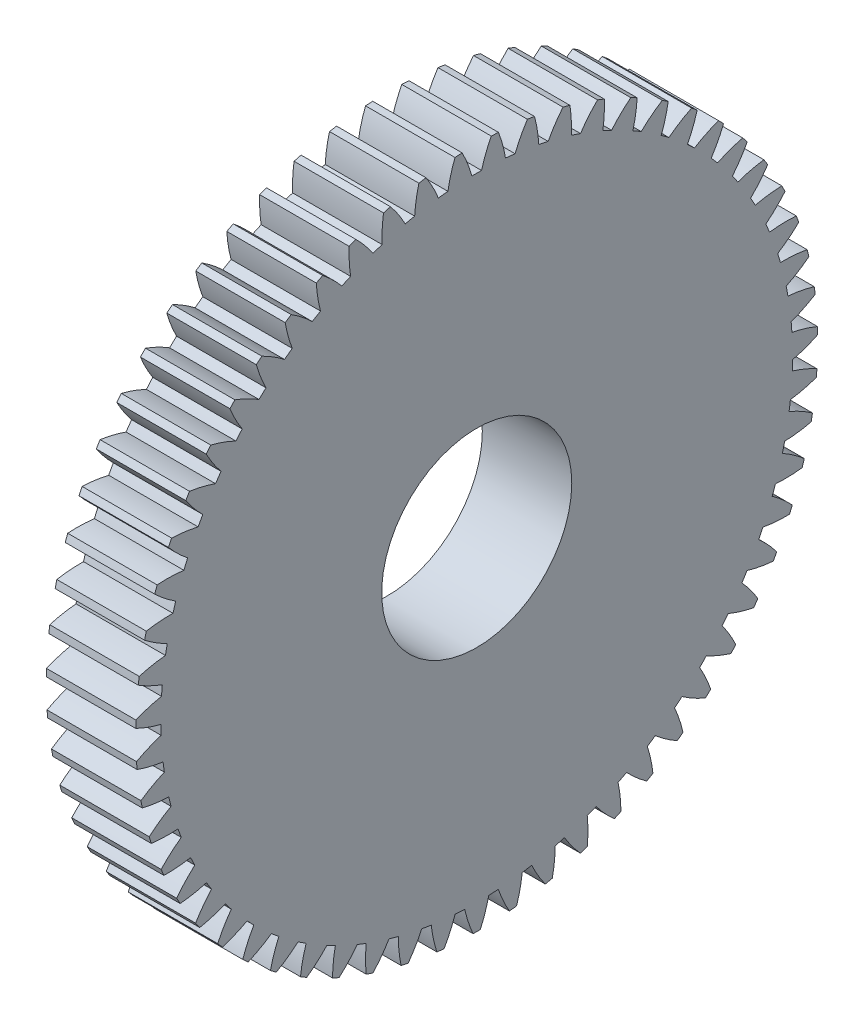
SolidWorks part; units mm, degrees
material "ABS PC"
ref_plane "Plane1" through (0, 0, 0) normal (0, 0, 1) x (1, 0, 0)
ref_plane "Plane2" through (0, 0, 0) normal (0, 1, 0) x (1, 0, 0)
ref_plane "Plane3" through (0, 0, 0) normal (1, 0, 0) x (0, 0, -1)
sketch "HoldingSke" plane through (0, 0, 0) normal (0, 1, 0) x (1, 0, 0)
  line L0 (0, 0) -> (1.0301, -1.7143)
  line L1 (-15, 0) -> (100, 0) construction
  line L2 (0, 0) -> (-2.1039, 2.3779)
  line L3 (0, 0) -> (-11.863, 4.5341)
  line L4 (0, 0) -> (4.4479, 7.4025)
  line L5 (0, 0) -> (-46.8476, -17.4728)
  line L6 (0, 0) -> (-3.3159, -2.2372)
  line L7 (-2.1039, 2.3779) -> (8.6586, 51.2059)
  line L8 (-76.2, 54.61) -> (-75.3, 54.61)
  line L9 (-71.009, 38.7566) -> (-53.1078, 45.2721)
  line L10 (-76.2, 71.12) -> (104.1128, 71.12)
  line L11 (0, 0) -> (-4, 0)
  line L12 (-76.2, 101.6) -> (-76.181, 101.6)
  line L13 (24.9733, 27.94) -> (52.9518, 28.4284)
  line L14 (24.9733, 27.94) -> (24.9743, 27.94)
  line L15 (24.9733, 27.94) -> (100.4006, 29.5858)
  line L16 (-63.627, -0.5) -> (-12.827, -0.5)
  circle A0 centre (0, 0) radius 2.5
  circle A1 centre (0, 0) radius 14.124
  circle A2 centre (0, 0) radius 37.5
  circle A3 centre (0, 0) radius 2.5
  dimension "MHD" = 28.248
  dimension "Hub_dia" = 75
  dimension "Bore" = 5
  dimension "MBD" = 5
  dimension "Num_teeth" = 59
  dimension "Pitch" = 2
  dimension "Overall_len" = 50
  dimension "Show_teeth" = 59
  dimension "Thickness" = 4
  dimension "OAL" = 50.0001
  dimension "T_dim" = 0.9
  dimension "Ap" = 20
  dimension "H" = 19.05
  dimension "Pitch_radius" = 180.3128
  dimension "Width" = 4
  dimension "Backlash" = 0.019
  dimension "Addendum_fac" = 1
  dimension "Dedendum_fac" = 1.25
  dimension "Clearance_fac" = 0.25
  dimension "Dedendum_add" = 0.001
  dimension "Module" = 0.5
sketch "BasProSke" plane through (0, 0, 0) normal (0, 1, 0) x (1, 0, 0)
  line L0 (-10, 0) -> (60, 0) construction
  line L1 (0, 0) -> (0, 15.25)
  line L2 (0, 0) -> (4, 0)
  line L3 (4, 0) -> (4, 15.25)
  line L4 (4, 15.25) -> (0, 15.25)
  dimension "Thickness" = 4
  dimension "Diameter" = 30.5
revolve "Base-Revolve" add sketch "BasProSke" angle 360 about L0
sketch "TooCutSke" plane through (0, 0, 0) normal (1, 0, 0) x (0, 0, -1)
  line L1 (0, 0) -> (0, 107) construction
  line L2 (0, 0) -> (-0.4259, 14.7438) construction
  line L3 (0, 0) -> (-1.5696, 29.4494) construction
  line L4 (-0.4259, 14.7438) -> (-0.7848, 14.7247) construction
  arc A0 (0.2153, 14.1224) -> (-0.2153, 14.1224) centre (0, 0) ccw
  arc A1 (0.6635, 15.261) -> (-0.6635, 15.261) centre (0, 0) ccw
  circle A2 centre (0, 0) radius 14.75 construction
  circle A3 centre (0, 0) radius 13.8605 construction
  arc A4 (-0.2153, 14.1224) -> (-0.6635, 15.261) centre (-5.8997, 12.5422) ccw
  arc A5 (0.6635, 15.261) -> (0.2153, 14.1224) centre (5.8997, 12.5422) ccw
  dimension "Root_dia" = 28.248
  dimension "Overcut_dia" = 30.5508
  dimension "Pitch_dia" = 29.5
  dimension "Base_dia" = 27.7209
  dimension "Flank_rad" = 5.9
  dimension "Half_ang" = 3.051
  dimension "Half_CT" = 0.3594
extrude "ToothCut" cut sketch "TooCutSke" along normal through all
fillet "Breaks" [suppressed] radius 0.01
fillet "RootFillets" [suppressed] radius 0.126
pattern_circular "TeethCuts" count 59 over 360 about axis through (0, 0, 0) along (1, 0, 0) of "ToothCut", "RootFillets", "Breaks"
sketch "HubNeaOneSke" plane through (0, 0, 0) normal (-1, 0, 0) x (0, 0, 1)
  circle A0 centre (0, 0) radius 14.124
  dimension "Diameter" = 28.248
extrude "HubNearOne" [suppressed] add sketch "HubNeaOneSke" along normal blind 46.0001
sketch "HubNeaBotSke" plane through (0, 0, 0) normal (-1, 0, 0) x (0, 0, 1)
  circle A0 centre (0, 0) radius 14.124
  dimension "Diameter" = 28.248
extrude "HubNearBoth" [suppressed] add sketch "HubNeaBotSke" along normal blind 23
ref_plane "FarPln" through (4, 0, 0) normal (1, 0, 0) x (0, 0, -1)
sketch "HubFarSke" plane through (4, 0, 0) normal (1, 0, 0) x (0, 0, -1)
  circle A0 centre (0, 0) radius 14.124
  dimension "Diameter" = 28.248
extrude "HubFar" [suppressed] add sketch "HubFarSke" along normal blind 23
sketch "BorSke" plane through (0, 0, 0) normal (1, 0, 0) x (0, 0, -1)
  circle A0 centre (0, 0) radius 2.5
  dimension "Diameter" = 5
extrude "Bore" cut sketch "BorSke" along normal mid plane 100.0001
sketch "KeySke" plane through (0, 0, 0) normal (1, 0, 0) x (0, 0, -1)
  line L0 (-1, 0) -> (-1, 3.4)
  line L1 (-1, 3.4) -> (1, 3.4)
  line L2 (1, 3.4) -> (1, 0)
  line L3 (0, 0) -> (0, 34) construction
  line L4 (-1, 0) -> (1, 0)
  dimension "Offset" = 3.4
  dimension "Width" = 2
extrude "Keyway" [suppressed] cut sketch "KeySke" along normal mid plane 100.0001
pattern_circular "Keyway2" [suppressed] count 2 every 90 about axis through (-10, 0, 0) along (1, 0, 0)
sketch "Sketch1" plane through (4, 0, 0) normal (1, 0, 0) x (0, 0, -1)
  circle A0 centre (0, 0) radius 4.25
  dimension "D1" = 8.5
extrude "Cut-Extrude1" cut sketch "Sketch1" against normal blind 10
equation "' \"Module@HoldingSke\" = 6.35"
equation "' \"Num_teeth@HoldingSke\" = 12"
equation "' \"Ap@HoldingSke\" =  20"
equation "' \"Ap@HoldingSke\" = 20"
equation "' \"Width@HoldingSke\" = 0.5 * 25.4"
equation "' \"Hub_dia@HoldingSke\"= 1 * 25.4"
equation "' \"Hub_dia@HoldingSke\" = 1 * 25.4"
equation "' \"Overall_len@HoldingSke\" = 1.0 * 25.4"
equation "' \"Bore@HoldingSke\" = 0.75 * 25.4"
equation "' \"T_dim@HoldingSke\" = 0.1 * 25.4"
equation "' \"Width@KeySke\" = 0.25 * 25.4"
equation "' \"Show_teeth@HoldingSke\" = 13"
equation "' \"Backlash@HoldingSke\" = 0.009 * 25.4"
equation "' \"Addendum_fac@HoldingSke\" = 1.0"
equation "' \"Dedendum_fac@HoldingSke\" = 1.25"
equation "' \"Dedendum_add@HoldingSke\" = 0.00005 * 25.4"
equation "' \"Clearance_fac@HoldingSke\" = 0.25"
equation "\"Pitch@HoldingSke\" = 1 / \"Module@HoldingSke\""
equation "\"Overcut_dia@TooCutSke\" = (\"Num_teeth@HoldingSke\" + 2 * \"Addendum_fac@HoldingSke\") / \"Pitch@HoldingSke\" + 0.002 * 25.4"
equation "\"Pitch_dia@TooCutSke\" = \"Num_teeth@HoldingSke\" / \"Pitch@HoldingSke\""
equation "\"Base_dia@TooCutSke\" = \"Num_teeth@HoldingSke\" / \"Pitch@HoldingSke\" * cos((\"Ap@HoldingSke\"  * 3.14159265 / 180))"
equation "\"Root_dia@TooCutSke\" = (\"Num_teeth@HoldingSke\" + 2) / \"Pitch@HoldingSke\" - 2 * (\"Addendum_fac@HoldingSke\" + \"Dedendum_fac@HoldingSke\") / \"Pitch@HoldingSke\" - \"Dedendum_add@HoldingSke\" * 2"
equation "\"Half_ang@TooCutSke\" = 180 / \"Num_teeth@HoldingSke\""
equation "\"Half_CT@TooCutSke\" = \"Num_teeth@HoldingSke\" / \"Pitch@HoldingSke\" * sin((3.14159265 / 2 / \"Num_teeth@HoldingSke\")) / 2 - 7 * \"Backlash@HoldingSke\" / 4"
equation "\"Flank_rad@TooCutSke\" = \"Num_teeth@HoldingSke\" / \"Pitch@HoldingSke\" / 5"
equation "\"Radius@RootFillets\" = \"Clearance_fac@HoldingSke\" / \"Pitch@HoldingSke\" + \"Dedendum_add@HoldingSke\""
equation "\"Break_rad@Breaks\" = 0.02 / \"Pitch@HoldingSke\""
equation "\"Thickness@HoldingSke\" = \"Width@HoldingSke\""
equation "\"OAL@HoldingSke\" = \"Thickness@HoldingSke\""
equation "\"MHD@HoldingSke\" = (\"Num_teeth@HoldingSke\" + 2) / \"Pitch@HoldingSke\" - 2 * (\"Addendum_fac@HoldingSke\" + \"Dedendum_fac@HoldingSke\")  / \"Pitch@HoldingSke\" - \"Dedendum_add@HoldingSke\" * 2"
equation "\"MBD@HoldingSke\" = (\"Num_teeth@HoldingSke\" + 2) / \"Pitch@HoldingSke\" - 2 * (\"Addendum_fac@HoldingSke\" + \"Dedendum_fac@HoldingSke\")  / \"Pitch@HoldingSke\" - \"Dedendum_add@HoldingSke\" * 2 - 0.002 * 25.4"
equation "\"MHD@HoldingSke\" = ((sgn( \"MHD@HoldingSke\" - \"Hub_dia@HoldingSke\" )-1)*( \"MHD@HoldingSke\" - \"Hub_dia@HoldingSke\" ))/-2+ \"Hub_dia@HoldingSke\""
equation "\"MBD@HoldingSke\" = ((sgn( \"MBD@HoldingSke\" - \"Bore@HoldingSke\" )-1)*( \"MBD@HoldingSke\" - \"Bore@HoldingSke\" ))/-2+ \"Bore@HoldingSke\""
equation "\"OAL@HoldingSke\" = ((sgn( \"OAL@HoldingSke\" - \"Overall_len@HoldingSke\" )+1)*( \"OAL@HoldingSke\" - \"Overall_len@HoldingSke\" ))/2 + \"Overall_len@HoldingSke\" + 0.000002 * 25.4"
equation "\"Num_teeth@TeethCuts\" = int( \"Show_teeth@HoldingSke\" ) + 1"
equation "\"Num_teeth@TeethCuts\" = ((sgn( \"Num_teeth@TeethCuts\" - \"Num_teeth@HoldingSke\" )-1)*( \"Num_teeth@TeethCuts\" - \"Num_teeth@HoldingSke\" ))/-2+ \"Num_teeth@HoldingSke\""
equation "\"Num_teeth@TeethCuts\" = ((sgn( \"Num_teeth@TeethCuts\" - 2.0)+1)*( \"Num_teeth@TeethCuts\" - 2.0))/2 +2.0"
equation "\"Angle@TeethCuts\" = 360.0 / \"Num_teeth@HoldingSke\""
equation "\"Diameter@BasProSke\" = (\"Num_teeth@HoldingSke\" + 2 * \"Addendum_fac@HoldingSke\") / \"Pitch@HoldingSke\""
equation "\"Thickness@BasProSke\"  = \"Thickness@HoldingSke\""
equation "' \"Fillet_rad@BasProSke\" =  \"Thickness@HoldingSke\" * 0.05"
equation "' \"Fillet_rad@BasProSke\" = \"Thickness@HoldingSke\" * 0.05"
equation "\"MHD@HoldingSke\" = ((sgn( \"MHD@HoldingSke\" - \"Root_dia@TooCutSke\" )-1)*( \"MHD@HoldingSke\" - \"Root_dia@TooCutSke\" ))/-2+ \"Root_dia@TooCutSke\""
equation "\"Diameter@HubNeaOneSke\" = \"MHD@HoldingSke\""
equation "\"Length@HubNearOne\" = \"OAL@HoldingSke\" - \"Thickness@BasProSke\""
equation "\"Diameter@HubNeaBotSke\" = \"MHD@HoldingSke\""
equation "\"Length@HubNearBoth\" = ( \"OAL@HoldingSke\" - \"Thickness@BasProSke\" ) / 2.0"
equation "\"Thickness@FarPln\" = \"Thickness@BasProSke\""
equation "\"Diameter@HubFarSke\" = \"MHD@HoldingSke\""
equation "\"Length@HubFar\" = ( \"OAL@HoldingSke\" - \"Thickness@BasProSke\" ) / 2.0"
equation "\"Diameter@BorSke\" = \"MBD@HoldingSke\""
equation "\"D1@Bore\" = \"OAL@HoldingSke\" * 2.0"
equation "\"D1@Keyway\" = \"OAL@HoldingSke\" * 2.0"
equation "\"Offset@KeySke\" = \"T_dim@HoldingSke\" + \"MBD@HoldingSke\" / 2.0"
